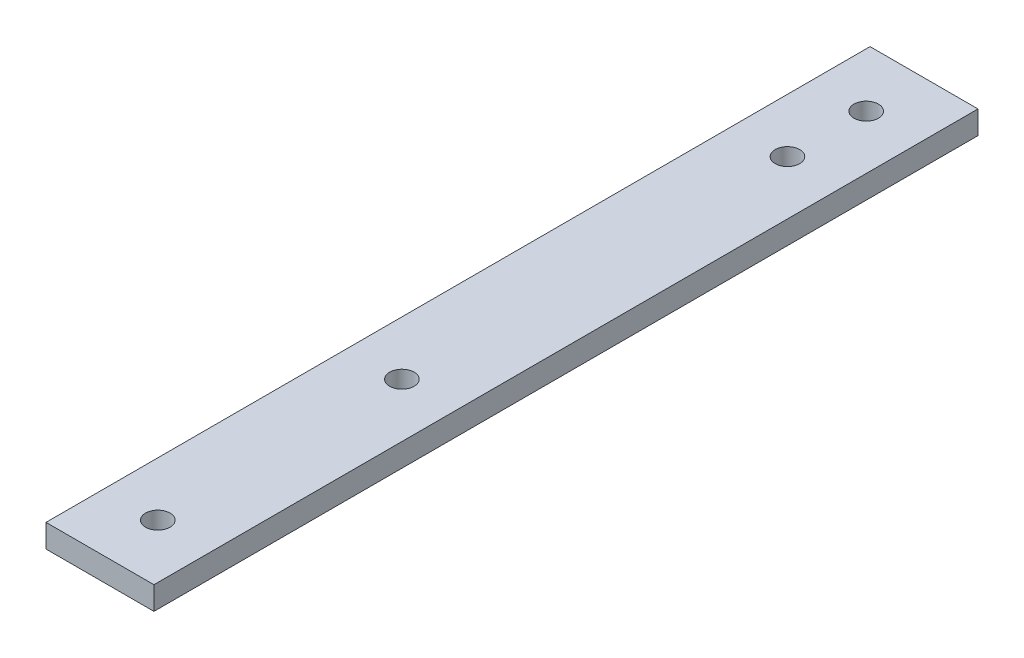
SolidWorks part; units mm, degrees
ref_plane "Front Plane" through (0, 0, 0) normal (0, 0, 1) x (1, 0, 0)
ref_plane "Top Plane" through (0, 0, 0) normal (0, 1, 0) x (1, 0, 0)
ref_plane "Right Plane" through (0, 0, 0) normal (1, 0, 0) x (0, 0, -1)
sketch "Sketch1" plane through (0, 0, 0) normal (0, 1, 0) x (1, 0, 0)
  line L0 (0, 0) -> (0, 106.86)
  line L1 (0, 106.86) -> (14, 106.86)
  line L2 (14, 106.86) -> (14, 0)
  line L3 (14, 0) -> (0, 0)
extrude "Extrude1" add sketch "Sketch1" along normal blind 3
sketch "Sketch2" plane through (0, 3, 0) normal (0, 1, 0) x (1, 0, 0)
  line L0 (7, 106.86) -> (7, 0) construction
  line L1 (14, 106.86) -> (0, 106.86) construction
  line L2 (0, 0) -> (14, 0) construction
  line L3 (0, 53.43) -> (14, 53.43) construction
  line L4 (0, 106.86) -> (0, 0) construction
  line L5 (14, 0) -> (14, 106.86) construction
sketch "Sketch3" plane through (0, 3, 0) normal (0, 1, 0) x (1, 0, 0)
  line L0 (7, 106.86) -> (7, 99.36) construction
  line L1 (7, 106.86) -> (7, 0) construction
  line L2 (0, 53.43) -> (14, 53.43) construction
  line L3 (0, 106.86) -> (0, 0) construction
  line L4 (7, 99.36) -> (7, 89.15) construction
  line L5 (7, 89.15) -> (7, 39.15) construction
  circle A0 centre (7, 99.36) radius 1.59
  circle A1 centre (7, 7.5) radius 1.59
  circle A2 centre (7, 89.15) radius 1.59
  circle A3 centre (7, 39.15) radius 1.59
extrude "Extrude3" cut sketch "Sketch3" against normal up to surface (3 mm away) up to face at (7, 0, -53.43)
